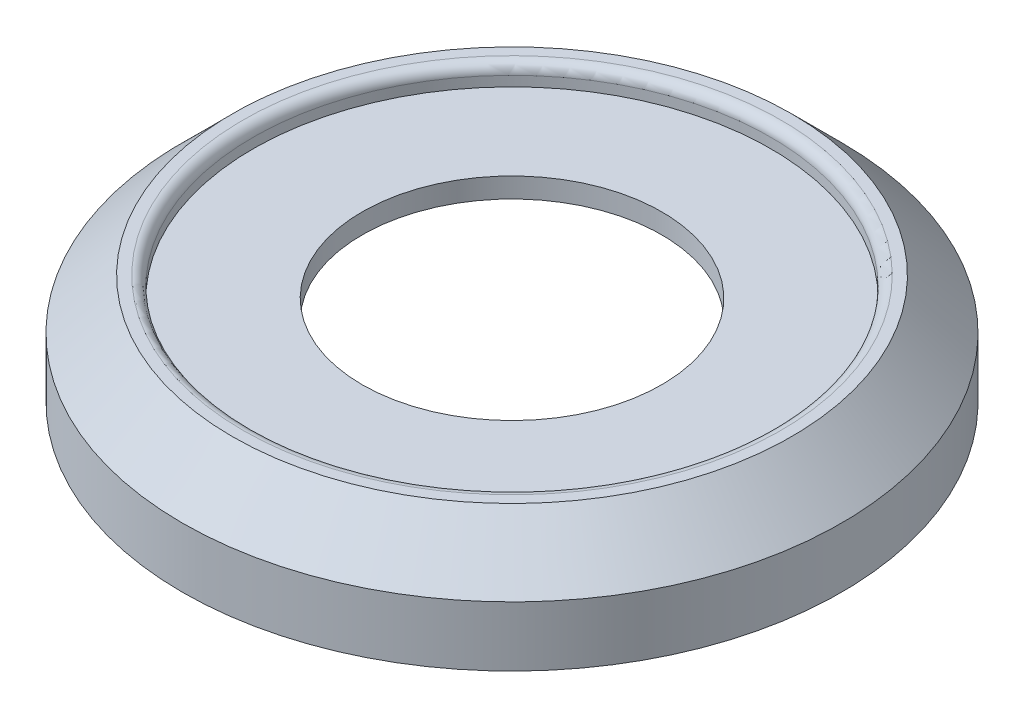
SolidWorks part; units mm, degrees
ref_plane "Ön Düzlem" through (0, 0, 0) normal (0, 0, 1) x (1, 0, 0)
ref_plane "Üst Düzlem" through (0, 0, 0) normal (0, 1, 0) x (1, 0, 0)
ref_plane "Sağ Düzlem" through (0, 0, 0) normal (1, 0, 0) x (0, 0, -1)
sketch "Çizim1" plane through (0, 0, 0) normal (0, 1, 0) x (1, 0, 0)
  circle A0 centre (0, 0) radius 33
  dimension "D1" = 66
extrude "Yükseklik-Ekstrüzyon1" add sketch "Çizim1" along normal blind 11
sketch "Çizim3" plane through (0, 0, 0) normal (0, -1, 0) x (1, 0, 0)
  circle A0 centre (0, 0) radius 31
  dimension "D1" = 62
extrude "Kes-Ekstrüzyon1" cut sketch "Çizim3" against normal blind 7
sketch "Çizim4" plane through (0, 11, 0) normal (0, 1, 0) x (1, 0, 0)
  circle A0 centre (0, 0) radius 25.925
  dimension "D1" = 51.85
extrude "Kes-Ekstrüzyon2" cut sketch "Çizim4" against normal blind 2
fillet "Radyus2" radius 1 1 edges at (0, 11, 25.925)
chamfer "Pah1" distance 5 angle 45 1 edges at (0, 11, 33)
sketch "Çizim5" plane through (0, 9, 0) normal (0, 1, 0) x (1, 0, 0)
  circle A0 centre (0, 0) radius 15
  dimension "D1" = 30
extrude "Kes-Ekstrüzyon3" cut sketch "Çizim5" against normal blind 2
